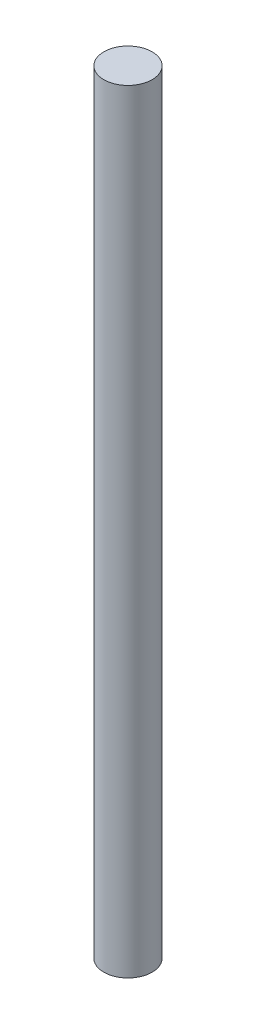
SolidWorks part; units mm, degrees
ref_plane "Front Plane" through (0, 0, 0) normal (0, 0, 1) x (1, 0, 0)
ref_plane "Top Plane" through (0, 0, 0) normal (0, 1, 0) x (1, 0, 0)
ref_plane "Right Plane" through (0, 0, 0) normal (1, 0, 0) x (0, 0, -1)
sketch "Sketch1" plane through (0, 0, 0) normal (0, 1, 0) x (1, 0, 0)
  circle A0 centre (0, 0) radius 2.5
  dimension "D1" = 5
extrude "Boss-Extrude1" add sketch "Sketch1" along normal blind 80
